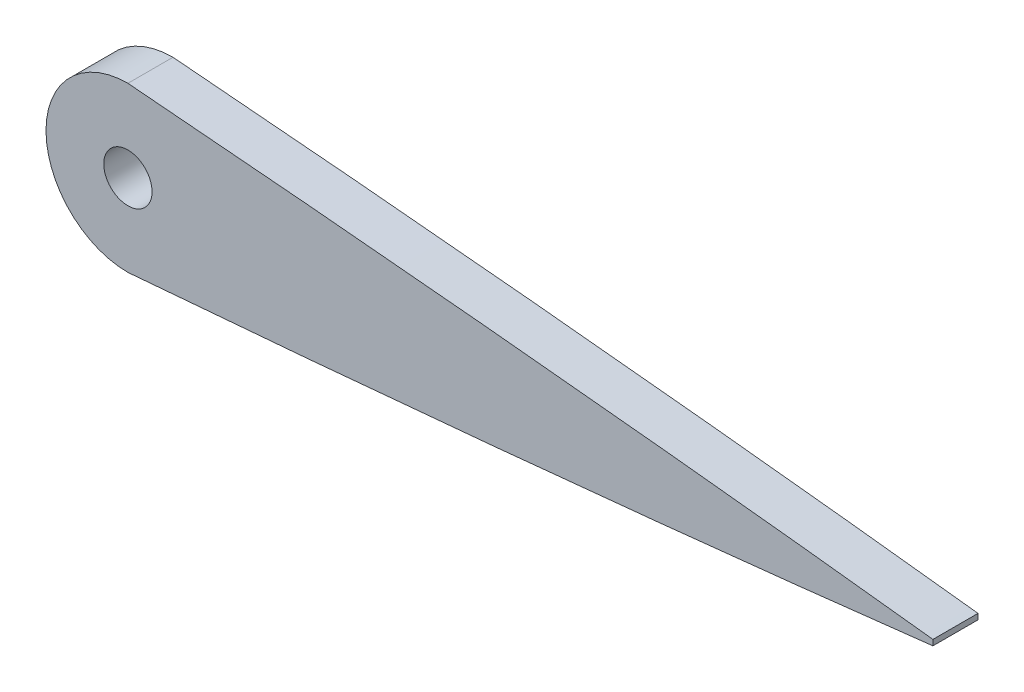
SolidWorks part; units mm, degrees
material "Фанера"
ref_plane "Спереди" through (0, 0, 0) normal (0, 0, 1) x (1, 0, 0)
ref_plane "Сверху" through (0, 0, 0) normal (0, 1, 0) x (1, 0, 0)
ref_plane "Справа" through (0, 0, 0) normal (1, 0, 0) x (0, 0, -1)
curve "Кривая1"
  spline degree 3 poles (200, 0.1747, 0) (199.6007, 0.2213, 0) (198.4854, 0.3514, 0) (196.462, 0.5838, 0) (193.7856, 0.8861, 0) (190.6579, 1.2319, 0) (187.1764, 1.6078, 0) (183.4067, 2.0045, 0) (179.3984, 2.4149, 0) (175.1909, 2.8335, 0) (170.8176, 3.2558, 0) (166.3067, 3.6778, 0) (161.6831, 4.0963, 0) (156.9692, 4.5083, 0) (152.1848, 4.9111, 0) (147.3484, 5.3022, 0) (142.4768, 5.6794, 0) (137.5855, 6.0402, 0) (132.6892, 6.3824, 0) (127.8016, 6.7038, 0) (122.9356, 7.0023, 0) (118.1034, 7.2757, 0) (113.3167, 7.5219, 0) (108.5864, 7.7388, 0) (103.9232, 7.9245, 0) (99.3373, 8.0772, 0) (94.8383, 8.1952, 0) (90.4357, 8.2769, 0) (86.1385, 8.321, 0) (81.9555, 8.3264, 0) (77.8951, 8.2921, 0) (73.9656, 8.2177, 0) (70.1749, 8.1027, 0) (66.5308, 7.947, 0) (63.0408, 7.751, 0) (59.7122, 7.515, 0) (56.5522, 7.2398, 0) (53.5677, 6.9266, 0) (50.7656, 6.5764, 0) (48.1524, 6.1907, 0) (45.7346, 5.7713, 0) (43.5185, 5.3197, 0) (41.5102, 4.8379, 0) (39.7154, 4.3278, 0) (38.1397, 3.791, 0) (36.7878, 3.2294, 0) (35.6652, 2.6441, 0) (34.771, 2.0345, 0) (34.119, 1.3968, 0) (33.6837, 0.7187, 0) (33.627, 0.2317, 0) (33.6, 0, 0) knots 0 0 0 0 0.007145 0.019956 0.036196 0.055011 0.075879 0.098429 0.122376 0.147488 0.173572 0.20046 0.228005 0.256076 0.284555 0.313333 0.34231 0.371393 0.400496 0.429538 0.458442 0.487136 0.515552 0.543624 0.57129 0.598491 0.62517 0.651272 0.676746 0.701542 0.725611 0.748908 0.771388 0.793008 0.813728 0.833508 0.85231 0.870097 0.886836 0.902493 0.917037 0.930441 0.94268 0.953734 0.96359 0.972247 0.979722 0.986065 0.991385 0.995901 1 1 1 1
curve "Кривая2"
  spline degree 3 poles (33.6, 0, 0) (33.627, -0.2317, 0) (33.6837, -0.7187, 0) (34.119, -1.3968, 0) (34.771, -2.0345, 0) (35.6652, -2.6441, 0) (36.7878, -3.2294, 0) (38.1397, -3.791, 0) (39.7154, -4.3278, 0) (41.5102, -4.8379, 0) (43.5185, -5.3197, 0) (45.7346, -5.7713, 0) (48.1524, -6.1907, 0) (50.7656, -6.5764, 0) (53.5677, -6.9266, 0) (56.5522, -7.2398, 0) (59.7122, -7.515, 0) (63.0408, -7.751, 0) (66.5308, -7.947, 0) (70.1749, -8.1027, 0) (73.9656, -8.2177, 0) (77.8951, -8.2921, 0) (81.9555, -8.3264, 0) (86.1385, -8.321, 0) (90.4357, -8.2769, 0) (94.8383, -8.1952, 0) (99.3373, -8.0772, 0) (103.9232, -7.9245, 0) (108.5864, -7.7388, 0) (113.3167, -7.5219, 0) (118.1034, -7.2757, 0) (122.9356, -7.0023, 0) (127.8016, -6.7038, 0) (132.6892, -6.3824, 0) (137.5855, -6.0402, 0) (142.4768, -5.6794, 0) (147.3484, -5.3022, 0) (152.1848, -4.9111, 0) (156.9692, -4.5083, 0) (161.6831, -4.0963, 0) (166.3067, -3.6778, 0) (170.8176, -3.2558, 0) (175.1909, -2.8335, 0) (179.3984, -2.4149, 0) (183.4067, -2.0045, 0) (187.1764, -1.6078, 0) (190.6579, -1.2319, 0) (193.7856, -0.8861, 0) (196.462, -0.5838, 0) (198.4854, -0.3514, 0) (199.6007, -0.2213, 0) (200, -0.1747, 0) knots 0 0 0 0 0.004099 0.008615 0.013935 0.020278 0.027753 0.03641 0.046266 0.05732 0.069559 0.082963 0.097507 0.113164 0.129903 0.14769 0.166492 0.186272 0.206992 0.228612 0.251092 0.274389 0.298458 0.323254 0.348728 0.37483 0.401509 0.42871 0.456376 0.484448 0.512864 0.541558 0.570462 0.599504 0.628607 0.65769 0.686667 0.715445 0.743924 0.771995 0.79954 0.826428 0.852512 0.877624 0.901571 0.924121 0.944989 0.963804 0.980044 0.992855 1 1 1 1
sketch "Эскиз1" plane through (0, 0, 0) normal (0, 0, 1) x (1, 0, 0)
  line L0 (200, 0.1747) -> (200, -0.1747)
  line L1 (97.6, -8.1212) -> (97.6, -5.0393)
  line L2 (97.6, -5.0393) -> (100.4, -5.0393)
  line L3 (100.4, -5.0393) -> (100.4, -8.0393)
  line L4 (124, 6.9352) -> (124, 3.7634)
  line L5 (124, 3.7634) -> (126.8, 3.7634)
  line L6 (126.8, 3.7634) -> (126.8, 6.7634)
  line L7 (63.6, 7.7774) -> (63.6, 4.7774)
  line L8 (63.6, 4.7774) -> (66.4, 4.7774)
  line L9 (66.4, 4.7774) -> (66.4, 7.9325)
  circle A0 centre (109, 0) radius 4
  circle A1 centre (55, 0) radius 4
  arc A2 (150, 5.0871) -> (150, -5.0871) centre (150, 0) ccw
  arc A3 (142.8797, 5.6459) -> (142.8797, -5.6459) centre (150, 0) ccw
  circle A5 centre (150, 0) radius 1.5
  spline S0 degree 3 poles (-8548.4207, -2696.178) (182.953, 74.4451) (26.4759, 10.5115) (34.119, -1.3968) (34.771, -2.0345) (35.6652, -2.6441) (36.7878, -3.2294) (38.1397, -3.791) (39.7154, -4.3278) (41.5102, -4.8379) (43.5185, -5.3197) (45.7346, -5.7713) (48.1524, -6.1907) (50.7656, -6.5764) (53.5677, -6.9266) (56.5522, -7.2398) (59.7122, -7.515) (63.0408, -7.751) (66.5308, -7.947) (70.1749, -8.1027) (73.9656, -8.2177) (77.8951, -8.2921) (81.9555, -8.3264) (86.1385, -8.321) (90.4357, -8.2769) (94.8383, -8.1952) (99.3373, -8.0772) (103.9232, -7.9245) (108.5864, -7.7388) (113.3167, -7.5219) (118.1034, -7.2757) (122.9356, -7.0023) (127.8016, -6.7038) (132.6892, -6.3824) (137.5855, -6.0402) (142.4768, -5.6794) (147.3484, -5.3022) (152.1848, -4.9111) (156.9692, -4.5083) (161.6831, -4.0963) (167.7684, -3.5455) (173.6854, -2.9833) (179.3984, -2.4149) (183.4067, -2.0045) (187.1764, -1.6078) (190.6579, -1.2319) (193.7856, -0.8861) (196.462, -0.5838) (330.7823, 14.847) (461.0153, 57.5532) (1632.4178, -8872.1577) knots -0.230755 -0.230755 -0.230755 -0.230755 0.004099 0.008615 0.013935 0.020278 0.027753 0.03641 0.046266 0.05732 0.069559 0.082963 0.097507 0.113164 0.129903 0.14769 0.166492 0.186272 0.206992 0.228612 0.251092 0.274389 0.298458 0.323254 0.348728 0.37483 0.401509 0.42871 0.456376 0.484448 0.512864 0.541558 0.570462 0.599504 0.628607 0.65769 0.686667 0.715445 0.743924 0.771995 0.79954 0.852512 0.877624 0.901571 0.924121 0.944989 0.963804 0.980044 0.992855 3.366631 3.366631 3.366631 3.366631 only from (33.6, 0) to (200, -0.1747) construction
  spline S1 degree 3 poles (2145.5431, 12838.4737) (494.7094, -69.0794) (348.0679, -16.8328) (196.462, 0.5838) (193.7856, 0.8861) (190.6579, 1.2319) (187.1764, 1.6078) (183.4067, 2.0045) (179.3984, 2.4149) (173.6854, 2.9833) (167.7684, 3.5455) (161.6831, 4.0963) (156.9692, 4.5083) (152.1848, 4.9111) (147.3484, 5.3022) (142.4768, 5.6794) (137.5855, 6.0402) (132.6892, 6.3824) (127.8016, 6.7038) (122.9356, 7.0023) (118.1034, 7.2757) (113.3167, 7.5219) (108.5864, 7.7388) (103.9232, 7.9245) (99.3373, 8.0772) (94.8383, 8.1952) (90.4357, 8.2769) (86.1385, 8.321) (81.9555, 8.3264) (77.8951, 8.2921) (73.9656, 8.2177) (70.1749, 8.1027) (66.5308, 7.947) (63.0408, 7.751) (59.7122, 7.515) (56.5522, 7.2398) (53.5677, 6.9266) (50.7656, 6.5764) (48.1524, 6.1907) (45.7346, 5.7713) (43.5185, 5.3197) (41.5102, 4.8379) (39.7154, 4.3278) (38.1397, 3.791) (36.7878, 3.2294) (35.6652, 2.6441) (34.771, 2.0345) (34.119, 1.3968) (25.5381, -11.9726) (224.7833, -91.3048) (-12351.3628, 3903.6371) knots -2.67585 -2.67585 -2.67585 -2.67585 0.007145 0.019956 0.036196 0.055011 0.075879 0.098429 0.122376 0.147488 0.20046 0.228005 0.256076 0.284555 0.313333 0.34231 0.371393 0.400496 0.429538 0.458442 0.487136 0.515552 0.543624 0.57129 0.598491 0.62517 0.651272 0.676746 0.701542 0.725611 0.748908 0.771388 0.793008 0.813728 0.833508 0.85231 0.870097 0.886836 0.902493 0.917037 0.930441 0.94268 0.953734 0.96359 0.972247 0.979722 0.986065 0.991385 0.995901 1.260778 1.260778 1.260778 1.260778 only from (200, 0.1747) to (33.6, 0) construction
  spline S2 degree 3 poles (33.6, 0) (33.627, -0.2317) (33.6837, -0.7187) (34.119, -1.3968) (34.771, -2.0345) (35.6652, -2.6441) (36.7878, -3.2294) (38.1397, -3.791) (39.7154, -4.3278) (41.5102, -4.8379) (43.5185, -5.3197) (45.7346, -5.7713) (48.1524, -6.1907) (50.7656, -6.5764) (53.5677, -6.9266) (56.5522, -7.2398) (59.7122, -7.515) (63.0408, -7.751) (66.5308, -7.947) (70.1749, -8.1027) (73.9656, -8.2177) (77.8951, -8.2921) (81.9555, -8.3264) (86.1385, -8.321) (90.4357, -8.2769) (94.2689, -8.2058) (96.6686, -8.1464) (97.6, -8.1212) knots 0 0 0 0 0.004099 0.008615 0.013935 0.020278 0.027753 0.03641 0.046266 0.05732 0.069559 0.082963 0.097507 0.113164 0.129903 0.14769 0.166492 0.186272 0.206992 0.228612 0.251092 0.274389 0.298458 0.323254 0.348728 0.37483 0.391389 0.391389 0.391389 0.391389
  spline S3 degree 3 poles (200, 0.1747) (199.6007, 0.2213) (198.4854, 0.3514) (196.462, 0.5838) (193.7856, 0.8861) (190.6579, 1.2319) (187.1764, 1.6078) (183.4067, 2.0045) (179.3984, 2.4149) (173.6854, 2.9833) (167.7684, 3.5455) (161.6831, 4.0963) (156.9692, 4.5083) (152.1848, 4.9111) (147.3484, 5.3022) (142.4768, 5.6794) (137.5855, 6.0402) (132.6892, 6.3824) (129.0934, 6.6189) (127.1312, 6.7427) (126.8, 6.7634) knots 0 0 0 0 0.007145 0.019956 0.036196 0.055011 0.075879 0.098429 0.122376 0.147488 0.20046 0.228005 0.256076 0.284555 0.313333 0.34231 0.371393 0.400496 0.429538 0.435436 0.435436 0.435436 0.435436
  spline S4 degree 3 poles (124, 6.9352) (123.6412, 6.9567) (121.6707, 7.0739) (118.1034, 7.2757) (113.3167, 7.5219) (108.5864, 7.7388) (103.9232, 7.9245) (99.3373, 8.0772) (94.8383, 8.1952) (90.4357, 8.2769) (86.1385, 8.321) (81.9555, 8.3264) (77.8951, 8.2921) (73.9656, 8.2177) (70.1749, 8.1027) (67.6688, 7.9956) (66.4269, 7.9339) (66.4, 7.9325) knots 0.452054 0.452054 0.452054 0.452054 0.458442 0.487136 0.515552 0.543624 0.57129 0.598491 0.62517 0.651272 0.676746 0.701542 0.725611 0.748908 0.771388 0.793008 0.793486 0.793486 0.793486 0.793486
  spline S5 degree 3 poles (100.4, -8.0393) (101.5657, -8.0027) (104.2872, -7.91) (108.5864, -7.7388) (113.3167, -7.5219) (118.1034, -7.2757) (122.9356, -7.0023) (127.8016, -6.7038) (132.6892, -6.3824) (137.5855, -6.0402) (142.4768, -5.6794) (147.3484, -5.3022) (152.1848, -4.9111) (156.9692, -4.5083) (161.6831, -4.0963) (167.7684, -3.5455) (173.6854, -2.9833) (179.3984, -2.4149) (183.4067, -2.0045) (187.1764, -1.6078) (190.6579, -1.2319) (193.7856, -0.8861) (196.462, -0.5838) (198.4854, -0.3514) (199.6007, -0.2213) (200, -0.1747) knots 0.407983 0.407983 0.407983 0.407983 0.42871 0.456376 0.484448 0.512864 0.541558 0.570462 0.599504 0.628607 0.65769 0.686667 0.715445 0.743924 0.771995 0.79954 0.852512 0.877624 0.901571 0.924121 0.944989 0.963804 0.980044 0.992855 1 1 1 1
  spline S6 degree 3 poles (63.6, 7.7774) (63.3962, 7.765) (62.0815, 7.683) (59.7122, 7.515) (56.5522, 7.2398) (53.5677, 6.9266) (50.7656, 6.5764) (48.1524, 6.1907) (45.7346, 5.7713) (43.5185, 5.3197) (41.5102, 4.8379) (39.7154, 4.3278) (38.1397, 3.791) (36.7878, 3.2294) (35.6652, 2.6441) (34.771, 2.0345) (34.119, 1.3968) (33.6837, 0.7187) (33.627, 0.2317) (33.6, 0) knots 0.810099 0.810099 0.810099 0.810099 0.813728 0.833508 0.85231 0.870097 0.886836 0.902493 0.917037 0.930441 0.94268 0.953734 0.96359 0.972247 0.979722 0.986065 0.991385 0.995901 1 1 1 1
  point P14 (99, -5.0393)
  point P20 (65, 4.7774)
  dimension "D1" = 8
  dimension "D2" = 8
  dimension "D16" = 5.0871
  dimension "D17" = 9.0871
  dimension "D18" = 3
  dimension "D3" = 75.4
  dimension "D4" = 21.4
  dimension "D5" = 2.8
  dimension "D6" = 2.8
  dimension "D7" = 10
  dimension "D8" = 15
  dimension "D9" = 3
  dimension "D10" = 3
  dimension "D11" = 2.8
  dimension "D12" = 10
  dimension "D13" = 3
  dimension "D14" = 116.4
  dimension "D15" = 10.1742
extrude "Бобышка-Вытянуть1" add sketch "Эскиз1" along normal mid plane 2.8 contours A2 S5 L0 S3 A5
equation "\"D3@Эскиз1\"=109-33.6"
equation "\"D16@Эскиз1\"=\"D15@Эскиз1\"/2"
equation "\"D17@Эскиз1\"=\"D16@Эскиз1\"+4"
